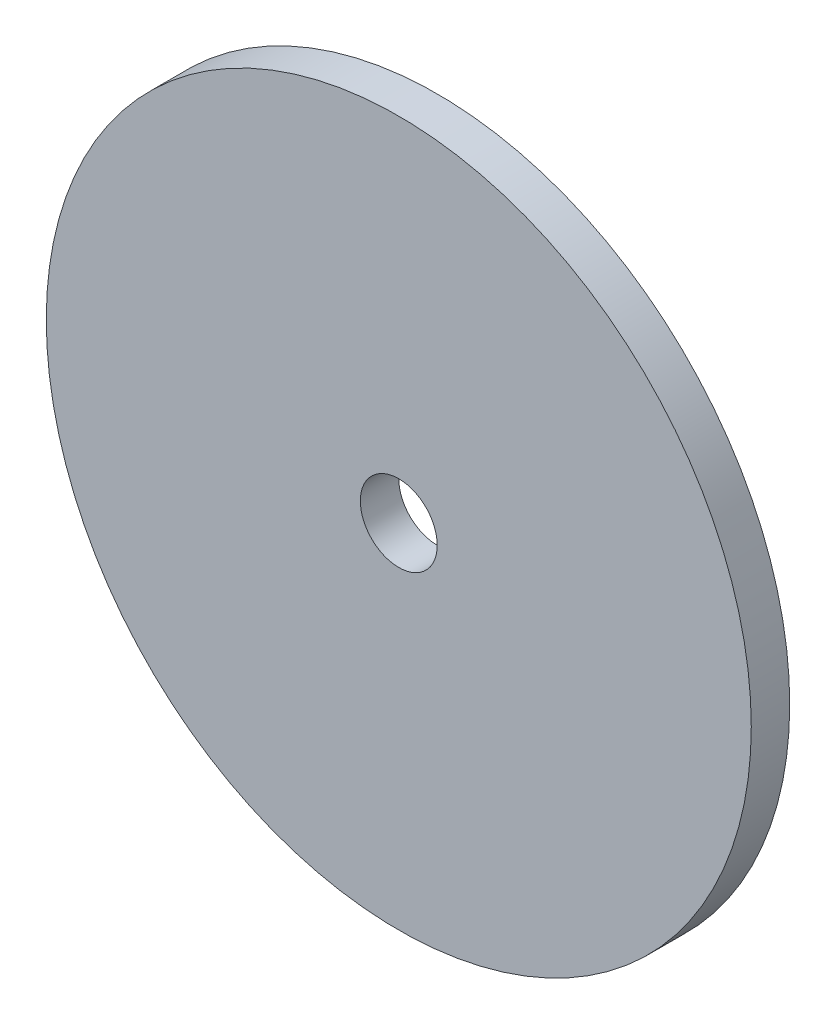
SolidWorks part; units mm, degrees
material "ASTM A36 Steel"
ref_plane "Front Plane" through (0, 0, 0) normal (0, 0, 1) x (1, 0, 0)
ref_plane "Top Plane" through (0, 0, 0) normal (0, 1, 0) x (1, 0, 0)
ref_plane "Right Plane" through (0, 0, 0) normal (1, 0, 0) x (0, 0, -1)
sketch "Sketch1" plane through (0, 0, 0) normal (0, 0, 1) x (1, 0, 0)
  circle A0 centre (0, 0) radius 55
  circle A1 centre (0, 0) radius 6
  dimension "D1" = 110
  dimension "D2" = 12
extrude "Boss-Extrude1" add sketch "Sketch1" along normal blind 6
